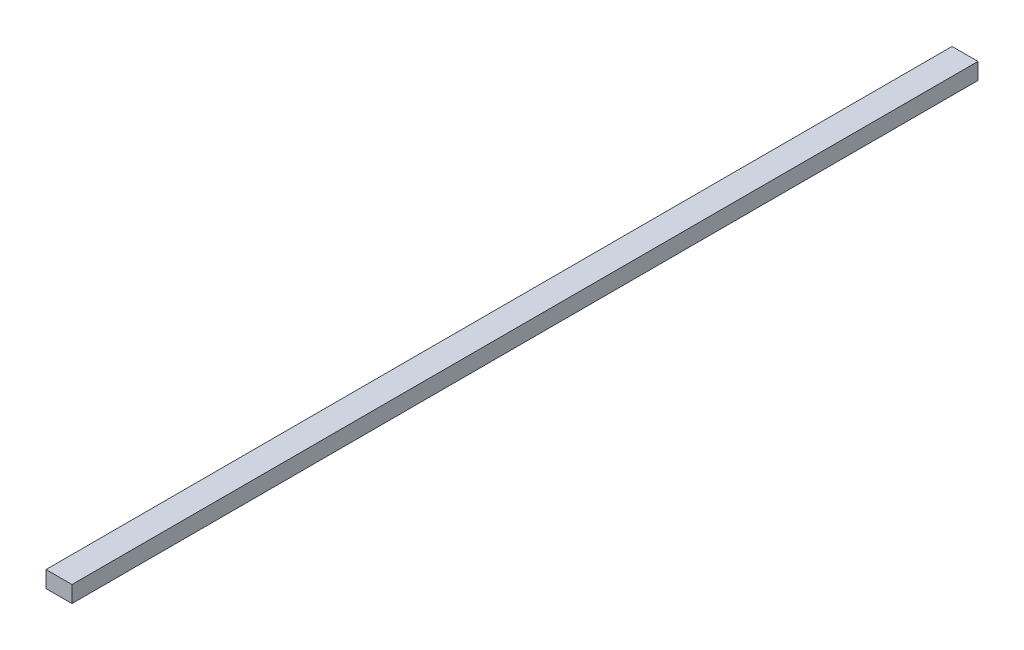
SolidWorks part; units mm, degrees
ref_plane "Front Plane" through (0, 0, 0) normal (0, 0, 1) x (1, 0, 0)
ref_plane "Top Plane" through (0, 0, 0) normal (0, 1, 0) x (1, 0, 0)
ref_plane "Right Plane" through (0, 0, 0) normal (1, 0, 0) x (0, 0, -1)
sketch "Sketch1" plane through (0, 0, 0) normal (0, 0, 1) x (1, 0, 0)
  line L1 (-69.85, 44.45) -> (69.85, 44.45)
  line L2 (-69.85, 44.45) -> (-69.85, -44.45)
  line L3 (-69.85, -44.45) -> (69.85, -44.45)
  line L4 (69.85, 44.45) -> (69.85, -44.45)
  line L5 (-69.85, 44.45) -> (69.85, -44.45) construction
  line L6 (-69.85, -44.45) -> (69.85, 44.45) construction
  point P0 (0, 0)
  dimension "D1" = 139.7
  dimension "D2" = 88.9
extrude "Boss-Extrude1" add sketch "Sketch1" along normal blind 4876.8
